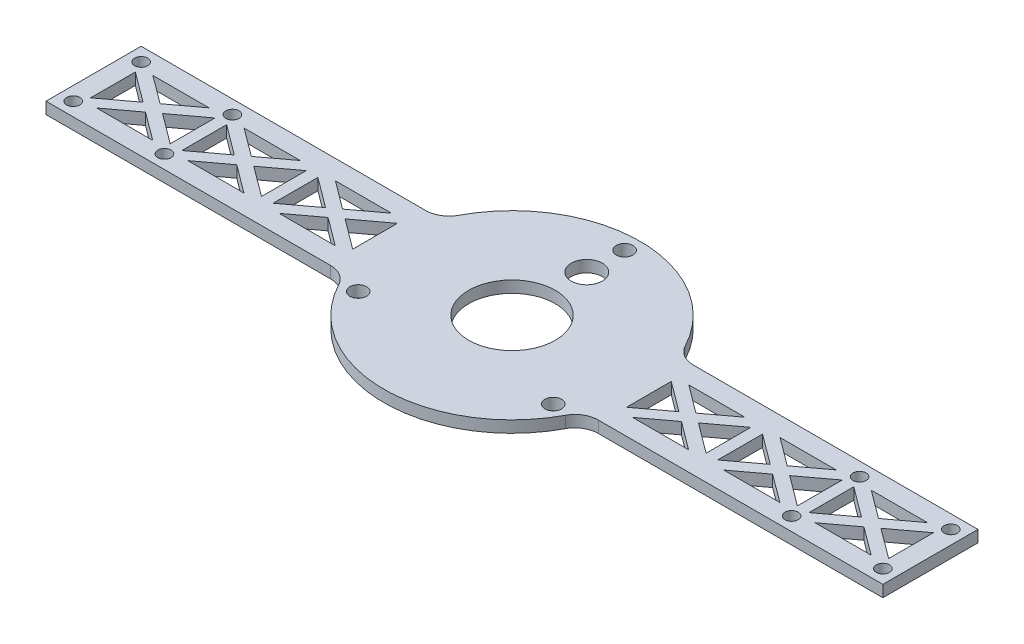
SolidWorks part; units mm, degrees
ref_plane "前视基准面" through (0, 0, 0) normal (0, 0, 1) x (1, 0, 0)
ref_plane "上视基准面" through (0, 0, 0) normal (0, 1, 0) x (1, 0, 0)
ref_plane "右视基准面" through (0, 0, 0) normal (1, 0, 0) x (0, 0, -1)
sketch "草图2" plane through (0, 0, 0) normal (0, 1, 0) x (1, 0, 0)
  line L0 (104.25, 47.4812) -> (104.25, -35.3147) construction
  line L1 (-11.2406, 8.75) -> (223.0481, 8.75) construction
  line L2 (0, 17.5) -> (23.5, 17.5) construction
  line L3 (0, 17.5) -> (0, 0) construction
  line L4 (0, 0) -> (23.5, 0) construction
  line L5 (23.5, 17.5) -> (23.5, 0) construction
  line L7 (-3.5, -3.5) -> (69.7835, -3.5)
  line L8 (-3.5, -3.5) -> (-3.5, 21)
  line L9 (-3.5, 21) -> (69.7835, 21)
  line L10 (212, -3.5) -> (212, 21)
  line L13 (11.75, -1.9939) -> (11.75, 8.75) construction
  line L17 (0, 0) -> (23.5, 17.5) construction
  line L18 (0, 17.5) -> (23.5, 0) construction
  line L19 (4.5257, 16) -> (18.9743, 16)
  line L20 (18.9743, 16) -> (11.75, 10.6202)
  line L21 (11.75, 10.6202) -> (4.5257, 16)
  line L22 (1.5, 14.5128) -> (1.5, 2.9872)
  line L23 (1.5, 2.9872) -> (9.2386, 8.75)
  line L24 (9.2386, 8.75) -> (1.5, 14.5128)
  line L31 (138.7165, 21) -> (212, 21)
  line L32 (138.7165, -3.5) -> (212, -3.5)
  line L33 (189.5257, 16) -> (196.75, 10.6202)
  line L38 (203.9743, 16) -> (189.5257, 16)
  line L39 (196.75, 10.6202) -> (203.9743, 16)
  line L40 (207, 2.9872) -> (199.2614, 8.75)
  line L41 (207, 14.5128) -> (207, 2.9872)
  line L42 (199.2614, 8.75) -> (207, 14.5128)
  line L43 (14.2614, 8.75) -> (22, 2.9872)
  line L44 (22, 2.9872) -> (22, 14.5128)
  line L45 (22, 14.5128) -> (14.2614, 8.75)
  line L46 (11.75, 6.8798) -> (18.9743, 1.5)
  line L47 (18.9743, 1.5) -> (4.5257, 1.5)
  line L48 (4.5257, 1.5) -> (11.75, 6.8798)
  line L49 (42.4743, 1.5) -> (28.0257, 1.5)
  line L50 (32.7386, 8.75) -> (25, 14.5128)
  line L51 (35.25, 10.6202) -> (28.0257, 16)
  line L52 (42.4743, 16) -> (35.25, 10.6202)
  line L53 (28.0257, 1.5) -> (35.25, 6.8798)
  line L54 (35.25, 6.8798) -> (42.4743, 1.5)
  line L55 (45.5, 14.5128) -> (37.7614, 8.75)
  line L56 (28.0257, 16) -> (42.4743, 16)
  line L57 (45.5, 2.9872) -> (45.5, 14.5128)
  line L58 (25, 14.5128) -> (25, 2.9872)
  line L59 (37.7614, 8.75) -> (45.5, 2.9872)
  line L60 (25, 2.9872) -> (32.7386, 8.75)
  line L61 (51.5257, 16) -> (65.9743, 16)
  line L62 (51.5257, 1.5) -> (58.75, 6.8798)
  line L63 (61.2614, 8.75) -> (69, 2.9872)
  line L64 (56.2386, 8.75) -> (48.5, 14.5128)
  line L65 (69, 14.5128) -> (61.2614, 8.75)
  line L66 (58.75, 10.6202) -> (51.5257, 16)
  line L67 (58.75, 6.8798) -> (65.9743, 1.5)
  line L68 (65.9743, 1.5) -> (51.5257, 1.5)
  line L69 (48.5, 2.9872) -> (56.2386, 8.75)
  line L70 (65.9743, 16) -> (58.75, 10.6202)
  line L71 (48.5, 14.5128) -> (48.5, 2.9872)
  line L72 (69, 2.9872) -> (69, 14.5128)
  line L73 (142.5257, 1.5) -> (156.9743, 1.5)
  line L74 (149.75, 6.8798) -> (142.5257, 1.5)
  line L75 (156.9743, 1.5) -> (149.75, 6.8798)
  line L76 (139.5, 14.5128) -> (147.2386, 8.75)
  line L77 (139.5, 2.9872) -> (139.5, 14.5128)
  line L78 (147.2386, 8.75) -> (139.5, 2.9872)
  line L79 (149.75, 10.6202) -> (156.9743, 16)
  line L80 (142.5257, 16) -> (149.75, 10.6202)
  line L81 (156.9743, 16) -> (142.5257, 16)
  line L82 (160, 2.9872) -> (152.2614, 8.75)
  line L83 (160, 14.5128) -> (160, 2.9872)
  line L84 (152.2614, 8.75) -> (160, 14.5128)
  line L85 (173.25, 6.8798) -> (166.0257, 1.5)
  line L86 (180.4743, 1.5) -> (173.25, 6.8798)
  line L87 (166.0257, 1.5) -> (180.4743, 1.5)
  line L88 (163, 2.9872) -> (163, 14.5128)
  line L89 (170.7386, 8.75) -> (163, 2.9872)
  line L90 (163, 14.5128) -> (170.7386, 8.75)
  line L91 (166.0257, 16) -> (173.25, 10.6202)
  line L92 (180.4743, 16) -> (166.0257, 16)
  line L93 (173.25, 10.6202) -> (180.4743, 16)
  line L94 (183.5, 2.9872) -> (175.7614, 8.75)
  line L95 (183.5, 14.5128) -> (183.5, 2.9872)
  line L96 (175.7614, 8.75) -> (183.5, 14.5128)
  line L97 (186.5, 2.9872) -> (186.5, 14.5128)
  line L98 (186.5, 14.5128) -> (194.2386, 8.75)
  line L99 (194.2386, 8.75) -> (186.5, 2.9872)
  line L100 (189.5257, 1.5) -> (203.9743, 1.5)
  line L101 (203.9743, 1.5) -> (196.75, 6.8798)
  line L102 (196.75, 6.8798) -> (189.5257, 1.5)
  circle A0 centre (0, 17.5) radius 1.7
  circle A1 centre (23.5, 17.5) radius 1.7
  circle A2 centre (0, 0) radius 1.7
  circle A3 centre (23.5, 0) radius 1.7
  circle A4 centre (104.25, 8.75) radius 11.15
  circle A5 centre (104.25, 28) radius 4
  circle A6 centre (104.25, 37.75) radius 2.15
  circle A9 centre (185, 0) radius 1.7
  circle A10 centre (208.5, 0) radius 1.7
  circle A11 centre (208.5, 17.5) radius 1.7
  circle A12 centre (185, 17.5) radius 1.7
  circle A13 centre (129.3647, -5.75) radius 2.15
  circle A14 centre (79.1353, -5.75) radius 2.15
  arc A15 (75.0861, -6.6923) -> (133.4139, -6.6923) centre (104.25, 8.75) ccw
  arc A16 (133.4139, 24.1923) -> (75.0861, 24.1923) centre (104.25, 8.75) ccw
  arc A17 (69.7835, 21) -> (75.0861, 24.1923) centre (69.7835, 27) ccw
  arc A18 (138.7165, 21) -> (133.4139, 24.1923) centre (138.7165, 27) cw
  arc A19 (69.7835, -3.5) -> (75.0861, -6.6923) centre (69.7835, -9.5) cw
  arc A20 (138.7165, -3.5) -> (133.4139, -6.6923) centre (138.7165, -9.5) ccw
  dimension "D1" = 23.5
  dimension "D2" = 104.25
  dimension "D5" = 3.4
  dimension "D3" = 22.3
  dimension "D6" = 8
  dimension "D7" = 4.3
  dimension "D8" = 19.25
  dimension "D9" = 29
  dimension "D12" = 66
  dimension "D15" = 3.5
  dimension "D23" = 12
  dimension "D24" = 23.5
  dimension "D4" = 17.5
  dimension "D10" = 8.75
  dimension "D13" = 3.5
  dimension "D14" = 3.5
  dimension "D16" = 1.5
  dimension "D17" = 1.5
  dimension "D18" = 1.5
  dimension "D19" = 1.5
  dimension "D20" = 11.75
  dimension "D21" = 1.5
  dimension "D22" = 2
  dimension "D28" = 215.5
  dimension "D11" = 3
extrude "凸台-拉伸1" add sketch "草图2" along normal blind 3
